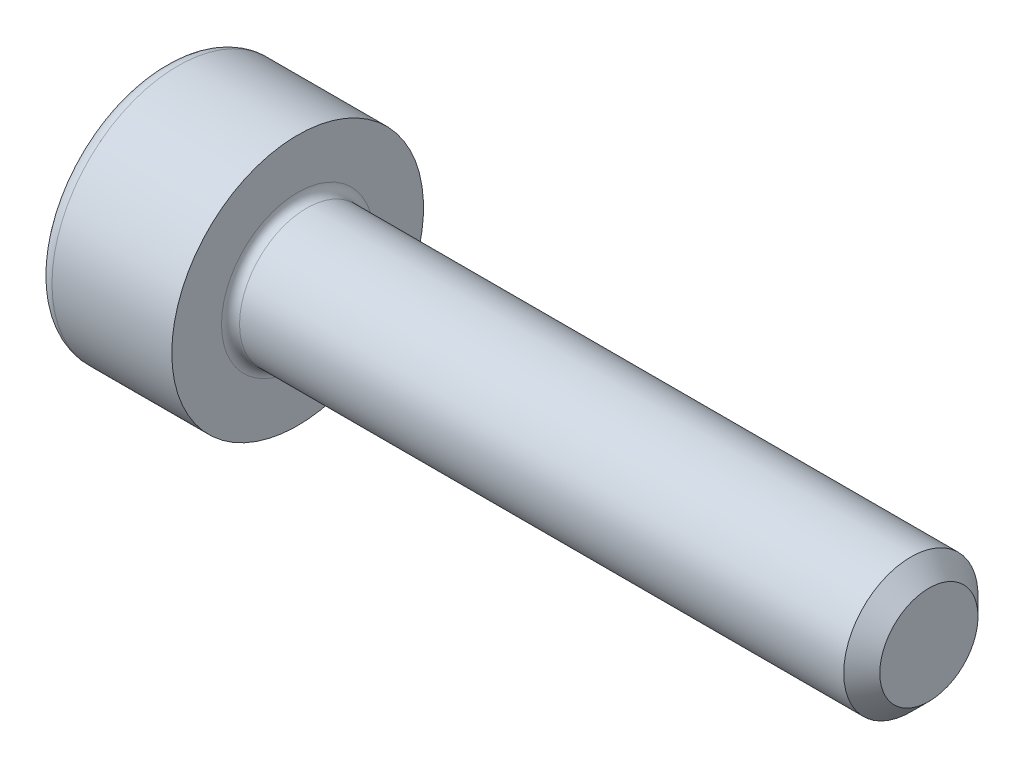
SolidWorks part; units mm, degrees
ref_plane "Спереди" through (0, 0, 0) normal (0, 0, 1) x (1, 0, 0)
ref_plane "Сверху" through (0, 0, 0) normal (0, 1, 0) x (1, 0, 0)
ref_plane "Справа" through (0, 0, 0) normal (1, 0, 0) x (0, 0, -1)
sketch "Sketch1" plane through (0, 0, 0) normal (0, 0, 1) x (1, 0, 0)
  line L0 (0, 0) -> (1.4887, 0)
  line L1 (1.4887, 0) -> (1.4887, 1.3957)
  line L2 (1.4887, 1.3957) -> (0, 1.3957)
  line L3 (0, 1.3957) -> (0, 0)
  line L4 (1.4887, 0) -> (8.4887, 0)
  line L5 (8.4887, 0) -> (8.4887, 0.7444)
  line L6 (8.4887, 0.7444) -> (1.4887, 0.7444)
  dimension "D1" = 7
revolve "Revolve1" add sketch "Sketch1" angle 360 about L0
fillet "Fillet1" radius 0.1 1 edges at (1.4887, 0, 0.7444)
fillet "Fillet2" radius 0.16 1 edges at (0, 0, 1.3957)
chamfer "Chamfer1" distance 0.2 angle 45 1 edges at (8.4887, 0, 0.7444)
sketch "Sketch2" plane through (0, 0, 0) normal (-1, 0, 0) x (0, 0, 1)
  line L1 (0, 0.8776) -> (-0.76, 0.4388)
  line L2 (-0.76, 0.4388) -> (-0.76, -0.4388)
  line L3 (-0.76, -0.4388) -> (0, -0.8776)
  line L4 (0, -0.8776) -> (0.76, -0.4388)
  line L5 (0.76, -0.4388) -> (0.76, 0.4388)
  line L6 (0.76, 0.4388) -> (0, 0.8776)
  circle A0 centre (0, 0) radius 0.76 construction
extrude "Extrude1" cut sketch "Sketch2" against normal blind 0.7
